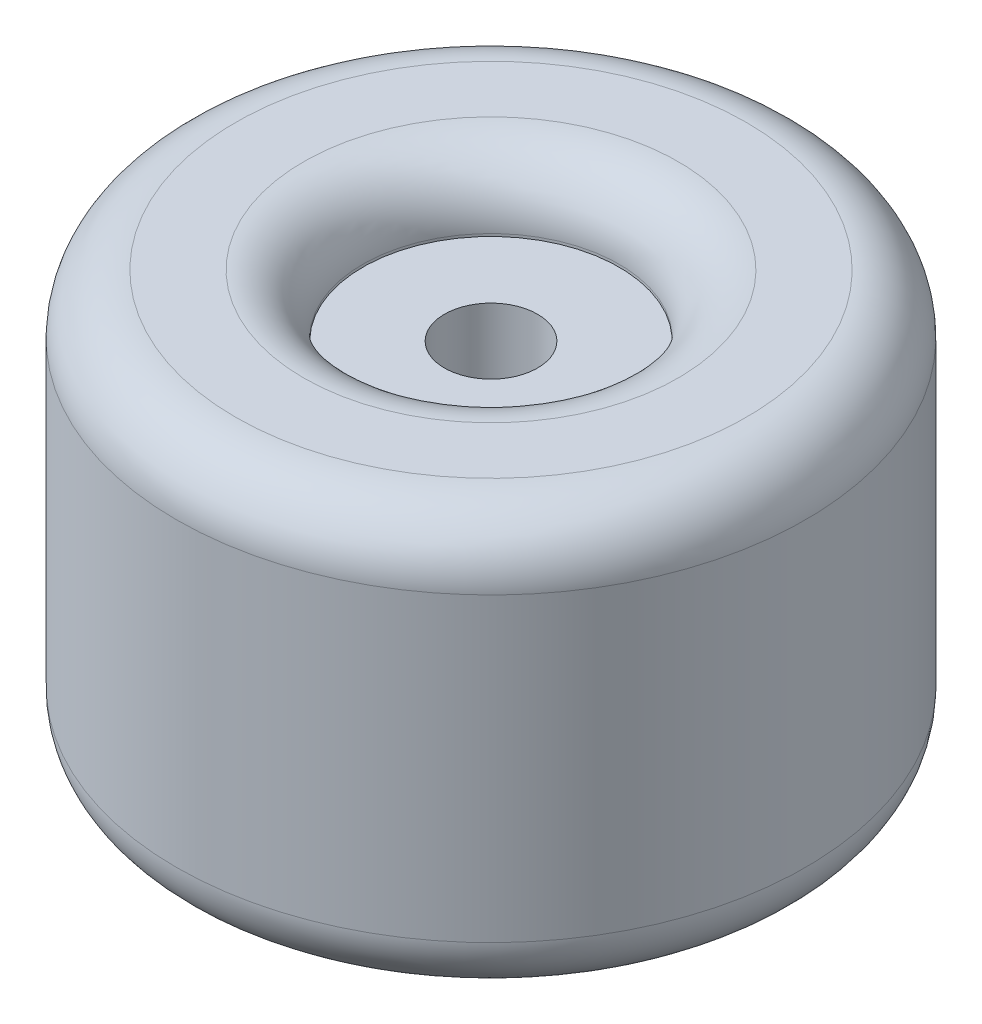
SolidWorks part; units mm, degrees
material "Polyester Resin"
ref_plane "Front Plane" through (0, 0, 0) normal (0, 0, 1) x (1, 0, 0)
ref_plane "Top Plane" through (0, 0, 0) normal (0, 1, 0) x (1, 0, 0)
ref_plane "Right Plane" through (0, 0, 0) normal (1, 0, 0) x (0, 0, -1)
sketch "Sketch1" plane through (0, 0, 0) normal (0, 0, 1) x (1, 0, 0)
  line L5 (0, 12.7) -> (0, -12.7)
  line L7 (11, 12.7) -> (11, 12.9194)
  line L8 (16.0797, 17.9994) -> (21.9197, 17.9997)
  line L9 (27, -12.9197) -> (27, 12.9197)
  line L10 (0, 12.7) -> (11, 12.7)
  line L11 (16.0797, -17.9994) -> (21.9197, -17.9997)
  line L12 (0, -12.7) -> (11, -12.7)
  line L13 (11, -12.7) -> (11, -12.9194)
  arc A0 (21.9197, 17.9997) -> (27, 12.9197) centre (21.92, 12.9197) cw
  arc A1 (11, 12.9194) -> (16.0797, 17.9994) centre (16.08, 12.9194) cw
  arc A2 (21.9197, -17.9997) -> (27, -12.9197) centre (21.92, -12.9197) ccw
  arc A3 (11, -12.9194) -> (16.0797, -17.9994) centre (16.08, -12.9194) ccw
  point P5 (27, 18)
  point P9 (27, 18)
  dimension "D5" = 5.08
  dimension "D6" = 5.08
  dimension "D2" = 11
revolve "Revolve3" add sketch "Sketch1" angle 360 about L5
sketch "Sketch2" plane through (0, -12.7, 0) normal (0, -1, 0) x (1, 0, 0)
  circle A0 centre (0, 0) radius 4
  dimension "D1" = 8
extrude "Cut-Extrude1" cut sketch "Sketch2" against normal blind 54.356
